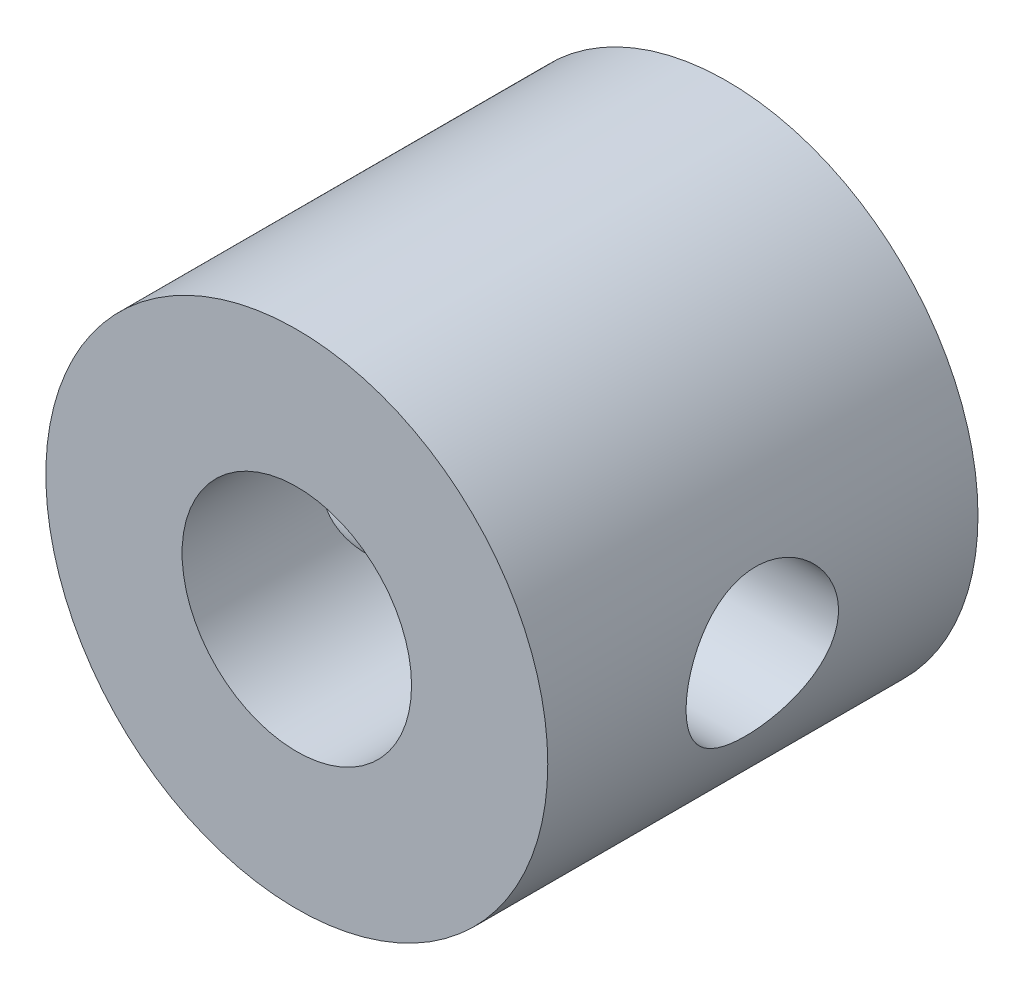
SolidWorks part; units mm, degrees
ref_plane "Front" through (0, 0, 0) normal (0, 0, 1) x (1, 0, 0)
ref_plane "Top" through (0, 0, 0) normal (0, 1, 0) x (1, 0, 0)
ref_plane "Right" through (0, 0, 0) normal (1, 0, 0) x (0, 0, -1)
sketch "Sketch1" plane through (0, 0, 0) normal (0, 0, 1) x (1, 0, 0)
  circle A0 centre (0, 0) radius 11.1125
  circle A1 centre (0, 0) radius 5.08
  dimension "D1" = 22.225
  dimension "D2" = 10.16
extrude "Boss-Extrude1" add sketch "Sketch1" along normal blind 19.05
chamfer "Chamfer1" [suppressed] distance 1.27 angle 60
sketch "Sketch5" plane through (0, 0, 0) normal (1, 0, 0) x (0, 0, -1)
  circle A0 centre (-9.525, -0.7148) radius 3.3655
  point P2 (0, 0)
  point P3 (0, 0)
extrude "Cut-Extrude3" cut sketch "Sketch5" against normal through all both and the other way through all
